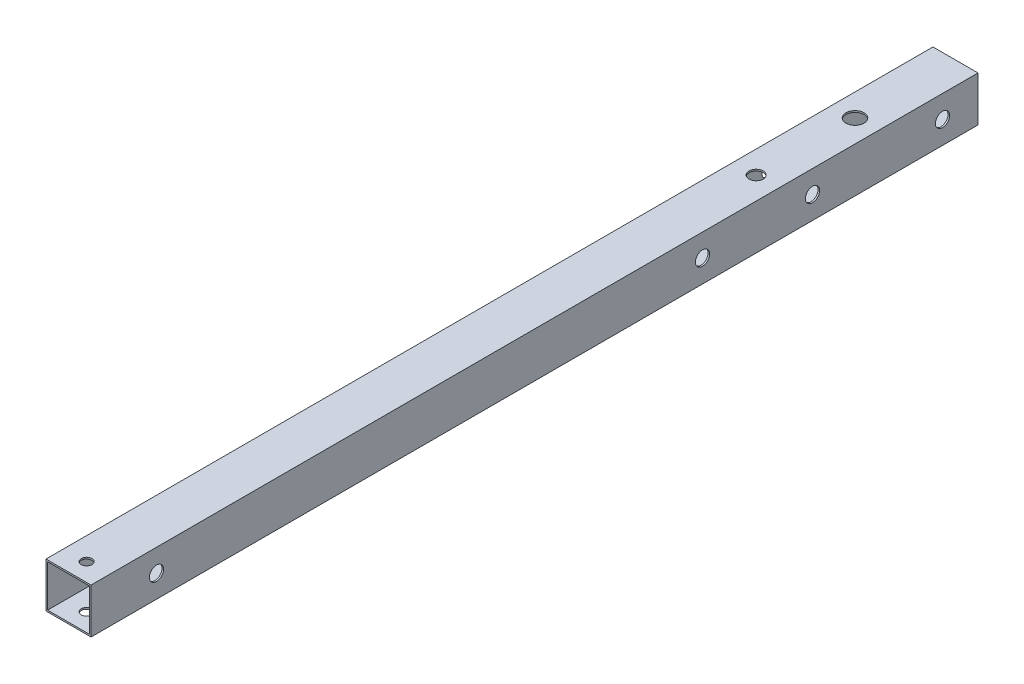
SolidWorks part; units mm, degrees
material "6061-T4 (SS)"
ref_plane "Front Plane" through (0, 0, 0) normal (0, 0, 1) x (1, 0, 0)
ref_plane "Top Plane" through (0, 0, 0) normal (0, 1, 0) x (1, 0, 0)
ref_plane "Right Plane" through (0, 0, 0) normal (1, 0, 0) x (0, 0, -1)
sketch "Sketch1" plane through (0, 0, 0) normal (0, 0, 1) x (1, 0, 0)
  line L1 (-12.7, 12.7) -> (12.7, 12.7)
  line L2 (-12.7, 12.7) -> (-12.7, -12.7)
  line L3 (-12.7, -12.7) -> (12.7, -12.7)
  line L4 (12.7, 12.7) -> (12.7, -12.7)
  line L5 (-12.7, 12.7) -> (12.7, -12.7) construction
  line L6 (-12.7, -12.7) -> (12.7, 12.7) construction
  point P0 (0, 0)
  dimension "D1" = 25.4
  dimension "D2" = 25.4
extrude "Extrude-Thin1" add sketch "Sketch1" along normal mid plane 500 thin
sketch "Sketch2" plane through (12.7, 0, 0) normal (1, 0, 0) x (0, 0, -1)
  line L0 (-250, 0) -> (250, 0) construction
  line L1 (-250, -12.7) -> (-250, 12.7) construction
  line L2 (250, -12.7) -> (250, 12.7) construction
  circle A0 centre (-237.3, 0) radius 3 construction
  circle A1 centre (156.7, 0) radius 4
  circle A2 centre (230, 0) radius 4
  circle A3 centre (94.7, 0) radius 4
  circle A4 centre (-213.12, 0) radius 4
  point P7 (-250, 0)
  dimension "D1" = 6
  dimension "D3" = 20
  dimension "D4" = 73.3
  dimension "D5" = 8
  dimension "D2" = 12.7
  dimension "D6" = 155.3
  dimension "D7" = 307.82
extrude "Cut-Extrude1" cut sketch "Sketch2" against normal through all
sketch "Sketch3" plane through (0, -12.7, 0) normal (0, -1, 0) x (1, 0, 0)
  line L0 (0, 250) -> (0, -250) construction
  line L1 (-12.7, 250) -> (12.7, 250) construction
  line L2 (-12.7, -250) -> (12.7, -250) construction
  circle A0 centre (0, 239.8) radius 3
  circle A1 centre (0, -137.65) radius 4
  circle A2 centre (0, -193.35) radius 5.1
  dimension "D1" = 6
  dimension "D3" = 8
  dimension "D5" = 10.2
  dimension "D2" = 10.2
  dimension "D4" = 112.35
  dimension "D6" = 56.65
extrude "Cut-Extrude2" cut sketch "Sketch3" against normal through all
